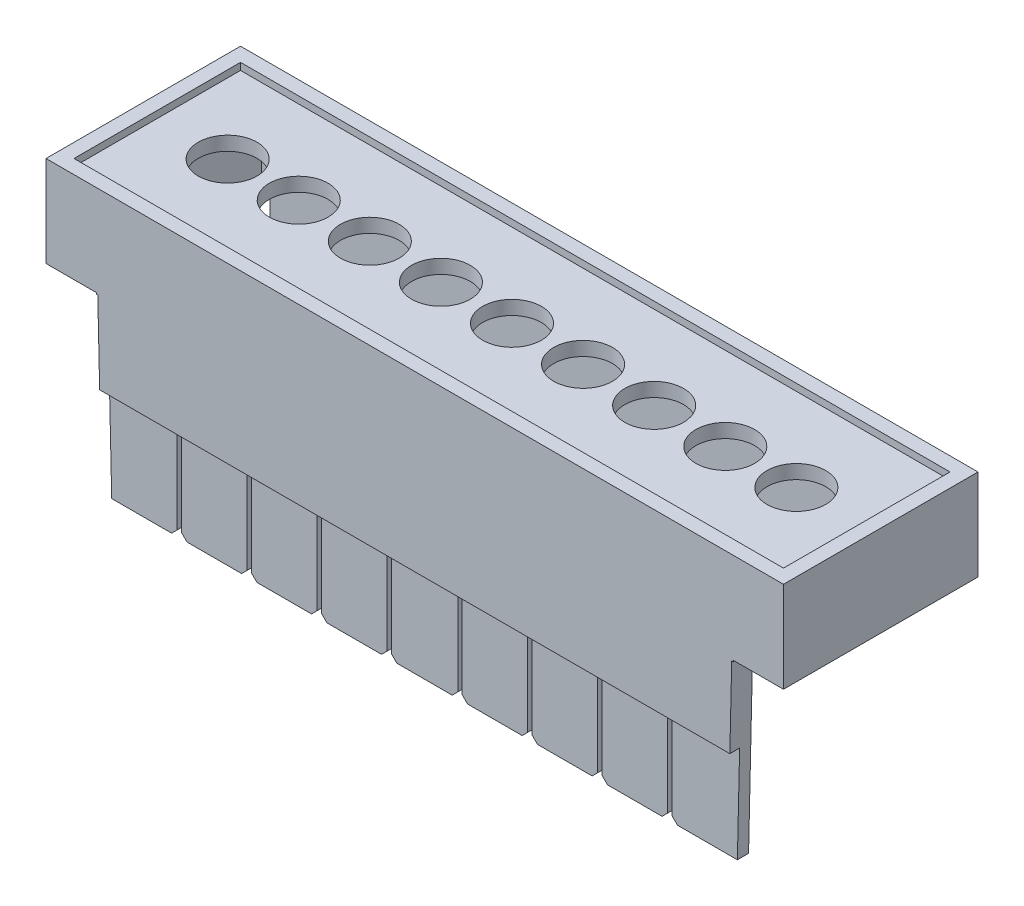
SolidWorks part; units mm, degrees
ref_plane "Спереди" through (0, 0, 0) normal (0, 0, 1) x (1, 0, 0)
ref_plane "Сверху" through (0, 0, 0) normal (0, 1, 0) x (1, 0, 0)
ref_plane "Справа" through (0, 0, 0) normal (1, 0, 0) x (0, 0, -1)
sketch "Эскиз1" plane through (0, 0, 0) normal (0, 1, 0) x (1, 0, 0)
  line L1 (26.35, -6.95) -> (-26.35, -6.95)
  line L2 (26.35, -6.95) -> (26.35, 6.95)
  line L3 (26.35, 6.95) -> (-26.35, 6.95)
  line L4 (-26.35, -6.95) -> (-26.35, 6.95)
  line L5 (26.35, -6.95) -> (-26.35, 6.95) construction
  line L6 (26.35, 6.95) -> (-26.35, -6.95) construction
  point P0 (0, 0)
  dimension "D1" = 52.7
  dimension "D2" = 13.9
extrude "Бобышка-Вытянуть1" add sketch "Эскиз1" along normal blind 11
sketch "Эскиз2" plane through (0, 0, 0) normal (0, -1, 0) x (1, 0, 0)
  line L0 (-26.35, 6.95) -> (26.35, 6.95) construction
  line L1 (23.35, -5.45) -> (-23.35, -5.45)
  line L2 (23.35, -5.45) -> (23.35, 5.45)
  line L3 (23.35, 5.45) -> (-23.35, 5.45)
  line L4 (-23.35, -5.45) -> (-23.35, 5.45)
  line L5 (23.35, -5.45) -> (-23.35, 5.45) construction
  line L6 (23.35, 5.45) -> (-23.35, -5.45) construction
  line L7 (-26.35, -6.95) -> (-26.35, 6.95) construction
  point P0 (0, 0)
  dimension "D1" = 1.5
  dimension "D2" = 3
extrude "Вырез-Вытянуть1" cut sketch "Эскиз2" against normal blind 9.5
sketch "Эскиз3" plane through (0, 0, 0) normal (0, -1, 0) x (1, 0, 0)
  line L0 (-26.35, 6.95) -> (26.35, 6.95) construction
  line L1 (-22.75, 6.95) -> (22.75, 6.95)
  line L2 (-22.75, 6.95) -> (-22.75, 5.45)
  line L3 (-22.75, 5.45) -> (22.75, 5.45)
  line L4 (22.75, 6.95) -> (22.75, 5.45)
  line L5 (23.35, 5.45) -> (-23.35, 5.45) construction
  dimension "D1" = 45.5
  dimension "D2" = 22.75
extrude "Бобышка-Вытянуть2" add sketch "Эскиз3" along normal blind 8.4
sketch "Эскиз4" plane through (22.75, 0, 0) normal (1, 0, 0) x (0, 0, -1)
  line L0 (-7.25, -8.9) -> (-6.25, -8.9)
  line L1 (-6.25, -8.9) -> (-6.25, -1.4)
  line L2 (-6.25, -1.4) -> (-7.25, -1.4)
  line L3 (-7.25, -1.4) -> (-7.25, -8.9)
  line L4 (-5.45, -8.4) -> (-5.45, 0) construction
  line L5 (-5.45, -8.4) -> (-6.95, -8.4) construction
  dimension "D1" = 0.8
  dimension "D2" = 7
  dimension "D3" = 0.5
  dimension "D4" = 1
  dimension "D5" = 1
extrude "Вырез-Вытянуть2" cut sketch "Эскиз4" against normal through all
sketch "Эскиз5" plane through (0, 0, 6.25) normal (0, 0, 1) x (1, 0, 0)
  line L0 (-2.675, -1.4) -> (-2.675, -8)
  line L1 (-22.75, -1.4) -> (22.75, -1.4) construction
  line L2 (-3.175, -8.5) -> (-3.675, -8.5)
  line L3 (-3.675, -8.5) -> (-3.675, -9.5)
  line L4 (-3.675, -9.5) -> (-1.375, -9.5)
  line L5 (-1.375, -9.5) -> (-1.375, -8.5)
  line L6 (-1.375, -8.5) -> (-1.875, -8.5)
  line L7 (-2.375, -8) -> (-2.375, -1.4)
  line L8 (-22.75, -1.4) -> (22.75, -1.4) construction
  line L9 (-2.375, -1.4) -> (-2.675, -1.4)
  line L11 (-22.75, -8.4) -> (22.75, -8.4) construction
  line L12 (-2.675, -8) -> (-3.175, -8.5)
  line L13 (-1.875, -8.5) -> (-2.375, -8)
  point P1 (-2.675, -8.5)
  point P9 (-2.375, -8.5)
  dimension "D2" = 0.3
  dimension "D3" = 1
  dimension "D4" = 1
  dimension "D5" = 0.1
  dimension "D6" = 1
  dimension "D7" = 2.375
extrude "Вырез-Вытянуть3" cut sketch "Эскиз5" against normal blind 3
pattern_linear "Линейный массив1" count 4 spacing 5 along (-1, 0, 0) of "Вырез-Вытянуть3"
sketch "Эскиз6" plane through (0, 0, 6.25) normal (0, 0, 1) x (1, 0, 0)
  line L0 (2.375, -1.4) -> (2.675, -1.4)
  line L1 (-22.75, -1.4) -> (22.75, -1.4) construction
  line L2 (-2.375, -1.4) -> (22.75, -1.4) construction
  line L3 (2.675, -1.4) -> (2.675, -8)
  line L4 (3.175, -8.5) -> (3.675, -8.5)
  line L5 (3.675, -8.5) -> (3.675, -9)
  line L6 (3.675, -9) -> (1.375, -9)
  line L7 (1.375, -9) -> (1.375, -8.5)
  line L8 (1.375, -8.5) -> (1.875, -8.5)
  line L9 (2.375, -8) -> (2.375, -1.4)
  line L10 (-1.975, -8.4) -> (22.75, -8.4) construction
  line L11 (1.875, -8.5) -> (2.375, -8)
  line L12 (2.675, -8) -> (3.175, -8.5)
  point P7 (2.675, -8.5)
  point P12 (2.375, -8.5)
  dimension "D1" = 0.3
  dimension "D2" = 0.1
  dimension "D3" = 1
  dimension "D4" = 1
  dimension "D5" = 0.5
  dimension "D6" = 2.375
extrude "Вырез-Вытянуть4" cut sketch "Эскиз6" against normal blind 3
pattern_linear "Линейный массив2" count 4 spacing 5 along (1, 0, 0) of "Вырез-Вытянуть4"
sketch "Эскиз7" plane through (0, 0, 6.95) normal (0, 0, 1) x (1, 0, 0)
  line L0 (-26.35, 11) -> (-26.35, 0) construction
  line L1 (-26.35, 4.5) -> (-22.75, 4.5)
  line L2 (-26.35, 4.5) -> (-26.35, -1)
  line L3 (-26.35, -1) -> (-22.75, -1)
  line L4 (-22.75, 4.5) -> (-22.75, -1)
  line L5 (-22.75, -8.4) -> (-22.75, -1.4) construction
  line L6 (-26.35, 11) -> (26.35, 11) construction
  line L7 (-26.35, 0) -> (-22.75, 0) construction
  line L8 (26.35, 11) -> (26.35, 0) construction
  line L9 (26.35, 4.5) -> (22.75, 4.5)
  line L10 (26.35, 4.5) -> (26.35, -1)
  line L11 (26.35, -1) -> (22.75, -1)
  line L12 (22.75, 4.5) -> (22.75, -1)
  line L13 (22.75, -8.4) -> (22.75, -1.4) construction
  line L14 (22.75, 0) -> (26.35, 0) construction
  dimension "D1" = 6.5
  dimension "D2" = 1
  dimension "D3" = 6.5
  dimension "D4" = 1
extrude "Вырез-Вытянуть5" cut sketch "Эскиз7" against normal through all
sketch "Эскиз8" plane through (0, 11, 0) normal (0, 1, 0) x (1, 0, 0)
  line L0 (26.35, 6.95) -> (-26.35, 6.95) construction
  line L1 (25.35, -5.95) -> (-25.35, -5.95)
  line L2 (25.35, -5.95) -> (25.35, 5.95)
  line L3 (25.35, 5.95) -> (-25.35, 5.95)
  line L4 (-25.35, -5.95) -> (-25.35, 5.95)
  line L5 (25.35, -5.95) -> (-25.35, 5.95) construction
  line L6 (25.35, 5.95) -> (-25.35, -5.95) construction
  line L7 (-26.35, 6.95) -> (-26.35, -6.95) construction
  point P0 (0, 0)
  dimension "D1" = 1
  dimension "D2" = 1
extrude "Вырез-Вытянуть6" cut sketch "Эскиз8" against normal blind 0.5
sketch "Эскиз9" plane through (0, 10.5, 0) normal (0, 1, 0) x (1, 0, 0)
  circle A0 centre (0, 0) radius 2.1
  dimension "D1" = 4.2
extrude "Вырез-Вытянуть7" cut sketch "Эскиз9" against normal blind 5
pattern_linear "Линейный массив3" count 5 spacing 5.08 along (-1, 0, 0) count 5 spacing 5.08 along (1, 0, 0) of "Вырез-Вытянуть7"
sketch "Эскиз10" plane through (0, 0, -6.95) normal (0, 0, -1) x (-1, 0, 0)
  line L0 (-26.35, 11) -> (26.35, 11) construction
  line L1 (-23.75, 1) -> (23.75, 1)
  line L2 (-23.75, 1) -> (-23.75, -1)
  line L3 (-23.75, -1) -> (23.75, -1)
  line L4 (23.75, 1) -> (23.75, -1)
  line L5 (-22.75, 4.5) -> (-22.75, 0) construction
  line L6 (22.75, 0) -> (22.75, 4.5) construction
  dimension "D1" = 10
  dimension "D2" = 1
  dimension "D3" = 1
  dimension "D4" = 2
extrude "Вырез-Вытянуть8" cut sketch "Эскиз10" against normal blind 3
sketch "Эскиз13" plane through (0, 0, 6.95) normal (0, 0, 1) x (1, 0, 0)
  line L0 (-26.35, 4.4) -> (-22.65, 4.4)
  line L1 (-22.65, 4.4) -> (-22.35, -8.6)
  line L2 (-22.35, -8.6) -> (-26.35, -8.6)
  line L3 (-26.35, -8.6) -> (-26.35, 4.4)
  line L4 (-22.75, 4.5) -> (-26.35, 4.5) construction
  line L6 (-22.75, -1.4) -> (-22.75, 4.5) construction
  line L7 (-22.75, -8.4) -> (-22.75, -1.4) construction
  line L8 (-22.75, -8.4) -> (-18.075, -8.4) construction
  line L9 (-26.35, 11) -> (-26.35, 4.5) construction
  dimension "D1" = 0.1
  dimension "D2" = 0.1
  dimension "D3" = 0.4
  dimension "D4" = 0.2
  dimension "D5" = 13
  dimension "D6" = 0
extrude "Вырез-Вытянуть9" cut sketch "Эскиз13" against normal blind 3
mirror "Зеркальное отражение1" about plane through (0, 0, 0) normal (1, 0, 0) of "Вырез-Вытянуть9"
